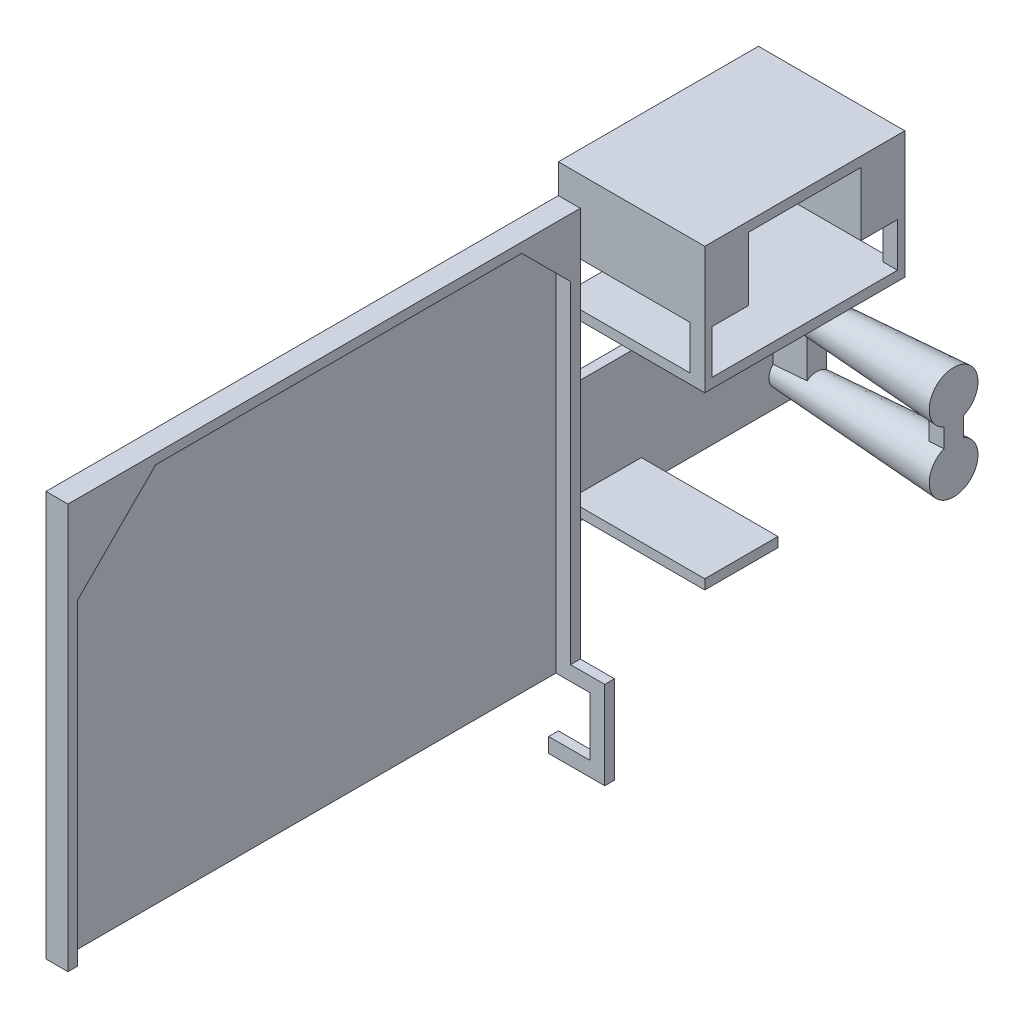
SolidWorks part; units mm, degrees
ref_plane "Front Plane" through (0, 0, 0) normal (0, 0, 1) x (1, 0, 0)
ref_plane "Top Plane" through (0, 0, 0) normal (0, 1, 0) x (1, 0, 0)
ref_plane "Right Plane" through (0, 0, 0) normal (1, 0, 0) x (0, 0, -1)
sketch "Sketch6" plane through (0, 0, 0) normal (1, 0, 0) x (0, 0, -1)
  line L1 (0, 0) -> (105, 0)
  line L2 (0, 0) -> (0, -83)
  line L3 (0, -83) -> (105, -83)
  line L4 (105, 0) -> (105, -83)
  dimension "D1" = 105
  dimension "D2" = 83
extrude "Boss-Extrude3" add sketch "Sketch6" along normal blind 4.5
sketch "Sketch9" plane through (0, -83, 0) normal (0, -1, 0) x (1, 0, 0)
  line L0 (4.5, 0) -> (4.5, -105) construction
  line L1 (0, 0) -> (0, -105) construction
  line L2 (4.5, -2) -> (1.5, -2)
  line L3 (4.5, -2) -> (4.5, -103)
  line L4 (4.5, -103) -> (1.5, -103)
  line L5 (1.5, -2) -> (1.5, -103)
  line L6 (4.5, 0) -> (0, 0) construction
  line L7 (4.5, -105) -> (0, -105) construction
  dimension "D1" = 1.5
  dimension "D2" = 2
  dimension "D3" = 2
extrude "Cut-Extrude6" cut sketch "Sketch9" against normal blind 81
sketch "Sketch10" plane through (0, 0, -2) normal (0, 0, -1) x (-1, 0, 0)
  line L1 (-4.5, -2) -> (-3.5, -2)
  line L2 (-4.5, -2) -> (-4.5, -10)
  line L3 (-4.5, -10) -> (-3.5, -10)
  line L4 (-3.5, -2) -> (-3.5, -10)
  dimension "D1" = 1
  dimension "D2" = 8
extrude "Boss-Extrude4" add sketch "Sketch10" along normal blind 8
sketch "Sketch11" plane through (0, 0, -103) normal (0, 0, 1) x (1, 0, 0)
  line L1 (4.5, -2) -> (3.2738, -2)
  line L2 (4.5, -2) -> (4.5, -7)
  line L3 (4.5, -7) -> (3.2738, -7)
  line L4 (3.2738, -2) -> (3.2738, -7)
  dimension "D1" = 5
extrude "Boss-Extrude5" add sketch "Sketch11" along normal blind 5
sketch "Sketch18" plane through (4.5, 0, 0) normal (1, 0, 0) x (0, 0, -1)
  line L0 (103, -12) -> (93, -2)
  line L1 (103, -7) -> (103, -83) construction
  line L2 (98, -2) -> (10, -2) construction
  line L3 (103, -12) -> (103, -2)
  line L4 (103, -2) -> (93, -2)
  line L5 (18, -2) -> (2, -2)
  line L6 (2, -2) -> (2, -18)
  line L7 (2, -10) -> (2, -83) construction
  line L8 (2, -18) -> (18, -2)
  dimension "D1" = 0
  dimension "D2" = 10
  dimension "D3" = 0
  dimension "D4" = 16
  dimension "D5" = 22.6274
extrude "Boss-Extrude12" add sketch "Sketch18" against normal up to vertex (1.2262 mm away)
sketch "Sketch27" plane through (0, 0, 0) normal (-1, 0, 0) x (0, 0, 1)
  line L0 (-105, -83) -> (-105, 0) construction
  line L1 (-105, -55) -> (-120, -55)
  line L2 (-105, -55) -> (-105, -53)
  line L3 (-105, -53) -> (-120, -53)
  line L4 (-120, -55) -> (-120, -53)
  line L5 (-125.5, -18) -> (-125.5, 21.7068) construction
  line L6 (-105, -20) -> (-146, -20)
  line L7 (-105, -20) -> (-105, -18)
  line L8 (-105, -18) -> (-146, -18)
  line L9 (-146, -20) -> (-146, -18)
  line L10 (-105, -9) -> (-114, -9)
  line L11 (-105, -9) -> (-105, 6)
  line L12 (-105, 6) -> (-114, 6)
  line L13 (-114, -9) -> (-114, 6)
  line L14 (-146, 6) -> (-137, 6)
  line L15 (-137, -9) -> (-137, 6)
  line L16 (-146, -9) -> (-137, -9)
  line L17 (-146, -9) -> (-146, 6)
  dimension "D1" = 15
  dimension "D2" = 28
  dimension "D3" = 63
  dimension "D4" = 41
  dimension "D5" = 2
  dimension "D6" = 2
  dimension "D7" = 9
  dimension "D8" = 15
  dimension "D9" = 9
extrude "Boss-Extrude20" add sketch "Sketch27" against normal blind 30
sketch "Sketch28" plane through (30, 0, 0) normal (1, 0, 0) x (0, 0, -1)
  line L0 (146, -9) -> (137, -9) construction
  line L1 (146, -20) -> (144.5, -20)
  line L2 (146, -20) -> (146, -9)
  line L3 (146, -9) -> (144.5, -9)
  line L4 (144.5, -20) -> (144.5, -9)
  line L5 (125.5, -18) -> (125.5, -4.7212) construction
  line L6 (105, -18) -> (146, -18) construction
  line L7 (105, -9) -> (106.5, -9)
  line L8 (106.5, -20) -> (106.5, -9)
  line L9 (105, -20) -> (106.5, -20)
  line L10 (105, -20) -> (105, -9)
  dimension "D1" = 1.5
extrude "Boss-Extrude21" add sketch "Sketch28" against normal blind 3
sketch "Sketch29" plane through (30, 0, 0) normal (1, 0, 0) x (0, 0, -1)
  line L0 (105, -20) -> (105, 6) construction
  line L1 (146, 6) -> (105, 6)
  line L2 (146, 6) -> (146, 4)
  line L3 (146, 4) -> (105, 4)
  line L4 (105, 6) -> (105, 4)
  dimension "D1" = 2
extrude "Boss-Extrude22" add sketch "Sketch29" against normal up to vertex (30 mm away)
sketch "Sketch30" plane through (0, 0, -105) normal (0, 0, -1) x (-1, 0, 0)
  line L0 (0, -83) -> (0, -55) construction
  line L1 (0, -58) -> (-2, -58)
  line L2 (0, -58) -> (0, -33)
  line L3 (0, -33) -> (-2, -33)
  line L4 (-2, -58) -> (-2, -33)
  dimension "D1" = 2
  dimension "D2" = 25
  dimension "D3" = 25
extrude "Boss-Extrude23" add sketch "Sketch30" along normal blind 50
sketch "Sketch31" plane through (2, 0, 0) normal (1, 0, 0) x (0, 0, -1)
  line L0 (155, -58) -> (105, -58) construction
  line L1 (155, -33) -> (155, -58) construction
  line L2 (155, -45.5) -> (129.1416, -45.5) construction
  circle A0 centre (149, -52) radius 5
  circle A1 centre (149, -39) radius 5
  dimension "D1" = 10
  dimension "D2" = 6
  dimension "D3" = 6
extrude "Boss-Extrude24" add sketch "Sketch31" along normal blind 35
draft "Draft1" type of draft neutral plane draft angle 3.5 faces to draft 1 face at (37, -52, -154) neutral plane through (37, -52, -149) neutral plane normal (1, 0, 0) reverse direction yes parameters "D1"=3.5
draft "Draft3" type of draft neutral plane draft angle 3.5 faces to draft 1 face at (37, -39, -144) neutral plane through (37, -39, -149) neutral plane normal (1, 0, 0) reverse direction yes parameters "D1"=3.5
sketch "Sketch32" plane through (2, 0, 0) normal (1, 0, 0) x (0, 0, -1)
  line L1 (151, -53) -> (147, -53)
  line L2 (151, -53) -> (151, -38)
  line L3 (151, -38) -> (147, -38)
  line L4 (147, -53) -> (147, -38)
  circle A0 centre (149, -52) radius 2.8593 construction
  circle A1 centre (149, -39) radius 2.8593 construction
  dimension "D1" = 2
  dimension "D2" = 2
  dimension "D3" = 1
  dimension "D4" = 1
  dimension "D5" = 2
extrude "Boss-Extrude25" add sketch "Sketch32" along normal blind 7
sketch "Sketch33" plane through (37, 0, 0) normal (1, 0, 0) x (0, 0, -1)
  line L1 (147, -39) -> (151, -39)
  line L2 (147, -39) -> (147, -52)
  line L3 (147, -52) -> (151, -52)
  line L4 (151, -39) -> (151, -52)
  circle A0 centre (149, -39) radius 5 construction
  circle A1 centre (149, -52) radius 5 construction
  point P6 (149, -39)
  dimension "D1" = 0
  dimension "D2" = 4
  dimension "D3" = 0
  dimension "D4" = 0
extrude "Boss-Extrude26" add sketch "Sketch33" against normal blind 3
sketch "Sketch34" plane through (4.5, 0, 0) normal (1, 0, 0) x (0, 0, -1)
  line L0 (105, -83) -> (105, -55) construction
  line L1 (103, -83) -> (105, -83)
  line L2 (103, -83) -> (103, -80)
  line L3 (103, -80) -> (105, -80)
  line L4 (105, -83) -> (105, -80)
  dimension "D1" = 3
extrude "Boss-Extrude27" add sketch "Sketch34" along normal blind 4
sketch "Sketch35" plane through (8.5, 0, 0) normal (1, 0, 0) x (0, 0, -1)
  line L0 (105, -83) -> (105, -80) construction
  line L1 (103, -80) -> (105, -80)
  line L2 (103, -80) -> (103, -95)
  line L3 (103, -95) -> (105, -95)
  line L4 (105, -80) -> (105, -95)
  dimension "D1" = 0
  dimension "D2" = 15
extrude "Boss-Extrude28" add sketch "Sketch35" along normal blind 3
sketch "Sketch36" plane through (0, -95, 0) normal (0, -1, 0) x (-1, 0, 0)
  line L0 (0, 0) -> (0, 105) construction
  line L1 (-11.5, 103) -> (0, 103)
  line L2 (-11.5, 103) -> (-11.5, 105)
  line L3 (-11.5, 105) -> (0, 105)
  line L4 (0, 103) -> (0, 105)
  dimension "D1" = 0
extrude "Boss-Extrude29" add sketch "Sketch36" along normal blind 3
